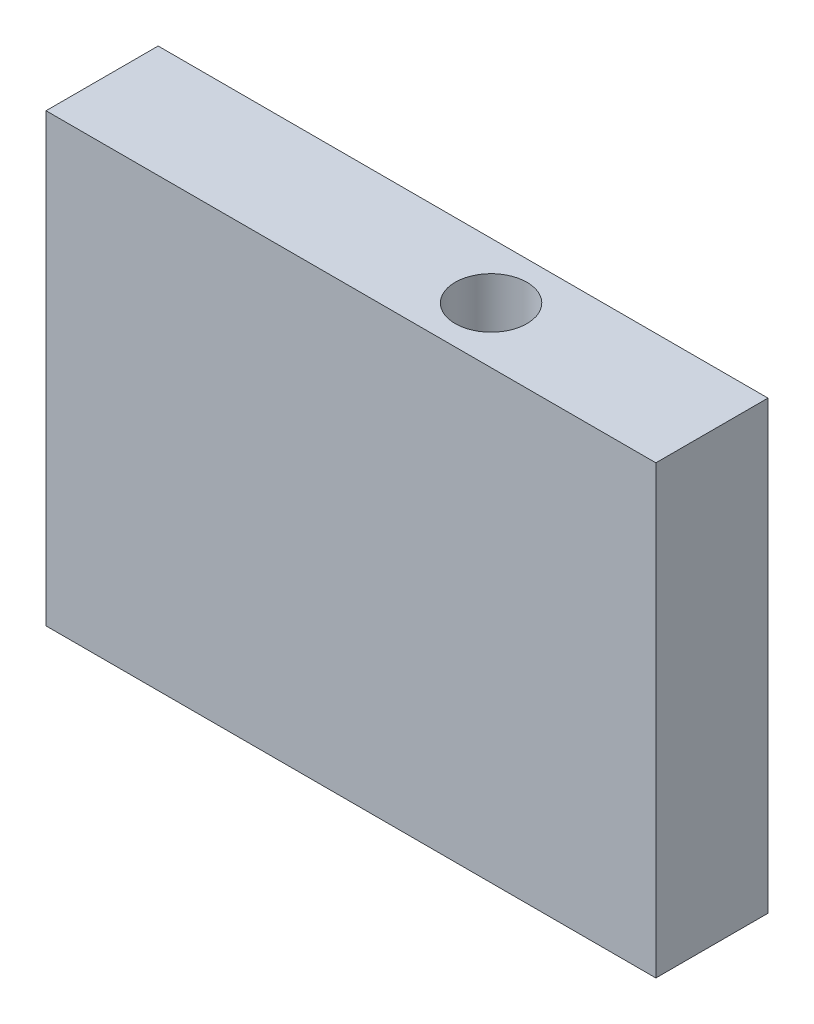
SolidWorks part; units mm, degrees
material "Alliage 1060"
ref_plane "Plan de face" through (0, 0, 0) normal (0, 0, 1) x (1, 0, 0)
ref_plane "Plan de dessus" through (0, 0, 0) normal (0, 1, 0) x (1, 0, 0)
ref_plane "Plan de droite" through (0, 0, 0) normal (1, 0, 0) x (0, 0, -1)
sketch "Esquisse1" plane through (0, 0, 0) normal (0, 0, 1) x (1, 0, 0)
  line L1 (0, 0) -> (-27.2, 0)
  line L2 (0, 0) -> (0, 19.9)
  line L3 (0, 19.9) -> (-27.2, 19.9)
  line L4 (-27.2, 0) -> (-27.2, 19.9)
  line L5 (8.2, 19.9) -> (-24.1513, 19.9) construction
  line L6 (-27.2, 0) -> (-27.2, 19.9) construction
extrude "Extrusion1" add sketch "Esquisse1" along normal blind 5
sketch "Esquisse2" plane through (0, 19.9, 0) normal (0, 1, 0) x (1, 0, 0)
  circle A0 centre (-9.85, -2.5) radius 1.6 construction
  circle A1 centre (-9.85, -2.5) radius 1.6
extrude "Enlèv. mat.-Extru.1" cut sketch "Esquisse2" against normal through all
